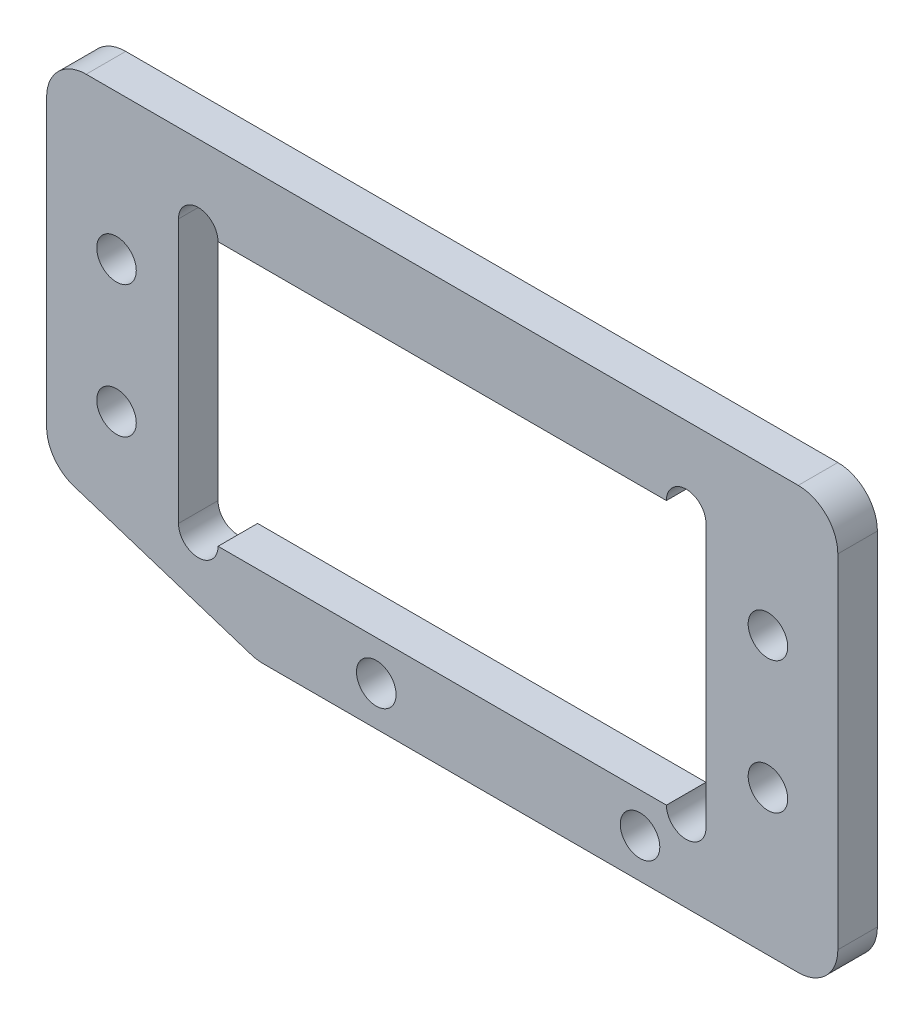
SolidWorks part; units mm, degrees
ref_plane "前视基准面" through (0, 0, 0) normal (0, 0, 1) x (1, 0, 0)
ref_plane "上视基准面" through (0, 0, 0) normal (0, 1, 0) x (1, 0, 0)
ref_plane "右视基准面" through (0, 0, 0) normal (1, 0, 0) x (0, 0, -1)
sketch "草图1" plane through (0, 0, 0) normal (0, 0, 1) x (1, 0, 0)
  line L0 (-4.7, -5) -> (-4.7, -15) construction
  line L1 (0, 0) -> (40, 0)
  line L2 (0, 0) -> (0, -20)
  line L3 (0, -20) -> (40, -20)
  line L4 (40, 0) -> (40, -20)
  line L5 (-10, 6) -> (50, 6)
  line L6 (-10, 6) -> (-10, -26)
  line L7 (-10, -26) -> (50, -26)
  line L8 (50, 6) -> (50, -26)
  line L9 (44.7, -5) -> (44.7, -15) construction
  line L10 (35, -23) -> (15, -23) construction
  circle A0 centre (-4.7, -5) radius 1.5
  circle A1 centre (-4.7, -15) radius 1.5
  circle A2 centre (44.7, -5) radius 1.5
  circle A3 centre (44.7, -15) radius 1.5
  circle A4 centre (35, -23) radius 1.5
  circle A5 centre (15, -23) radius 1.5
  dimension "D6" = 3
  dimension "D1" = 40
  dimension "D2" = 20
  dimension "D3" = 10
  dimension "D4" = 4.7
  dimension "D5" = 5
  dimension "D7" = 10
  dimension "D8" = 5
  dimension "D9" = 4.7
  dimension "D10" = 10
  dimension "D11" = 10
  dimension "D12" = 6
  dimension "D13" = 6
  dimension "D14" = 20
  dimension "D15" = 15
  dimension "D16" = 3
extrude "凸台-拉伸1" add sketch "草图1" along normal blind 3
sketch "草图2" plane through (0, 0, 3) normal (0, 0, 1) x (1, 0, 0)
  line L0 (40, 0) -> (0, 0) construction
  line L1 (0, -20) -> (40, -20) construction
  circle A0 centre (1.5, 0) radius 1.5
  circle A1 centre (38.5, 0) radius 1.5
  circle A2 centre (38.5, -20) radius 1.5
  circle A3 centre (1.5, -20) radius 1.5
  dimension "D1" = 3
extrude "切除-拉伸1" cut sketch "草图2" against normal blind 3
fillet "圆角1" radius 3 4 edges at (50, 6, 1.5) (50, -26, 1.5) (-10, 6, 1.5) (-10, -26, 1.5)
sketch "草图3" plane through (0, 0, 0) normal (0, 0, -1) x (-1, 0, 0)
  line L0 (-5.9462, -26) -> (10, -20.8534)
  line L1 (7, -26) -> (-47, -26) construction
  line L2 (10, 3) -> (10, -23) construction
  line L3 (10, -20.8534) -> (15.4892, -37.2737)
  line L4 (15.4892, -37.2737) -> (-5.9462, -26)
extrude "切除-拉伸2" cut sketch "草图3" against normal blind 10
fillet "圆角2" radius 3 2 edges at (-10, -20.8534, 1.5) (5.9462, -26, 1.5)
